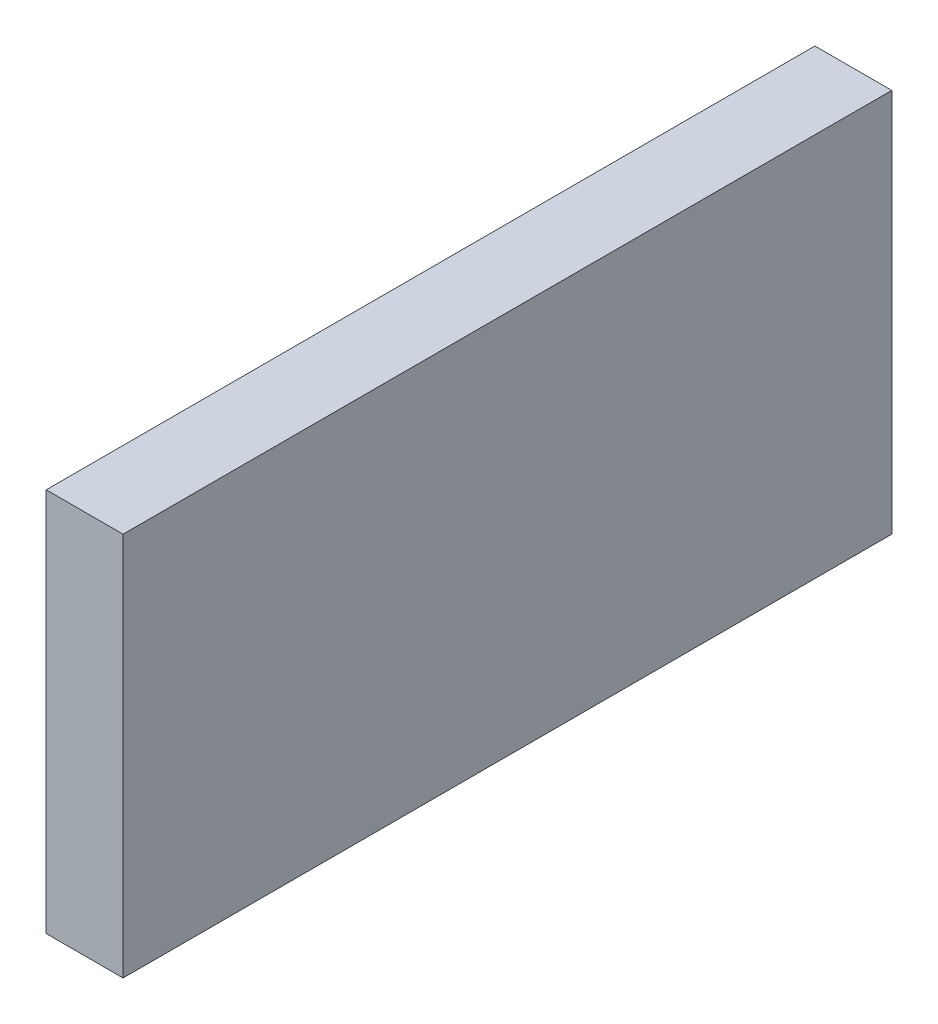
SolidWorks part; units mm, degrees
ref_plane "Front Plane" through (0, 0, 0) normal (0, 0, 1) x (1, 0, 0)
ref_plane "Top Plane" through (0, 0, 0) normal (0, 1, 0) x (1, 0, 0)
ref_plane "Right Plane" through (0, 0, 0) normal (1, 0, 0) x (0, 0, -1)
sketch "Sketch1" plane through (0, 0, 0) normal (1, 0, 0) x (0, 0, -1)
  line L1 (0, 0) -> (40, 0)
  line L2 (0, 0) -> (0, 20)
  line L3 (0, 20) -> (40, 20)
  line L4 (40, 0) -> (40, 20)
extrude "Boss-Extrude1" add sketch "Sketch1" along normal blind 4
